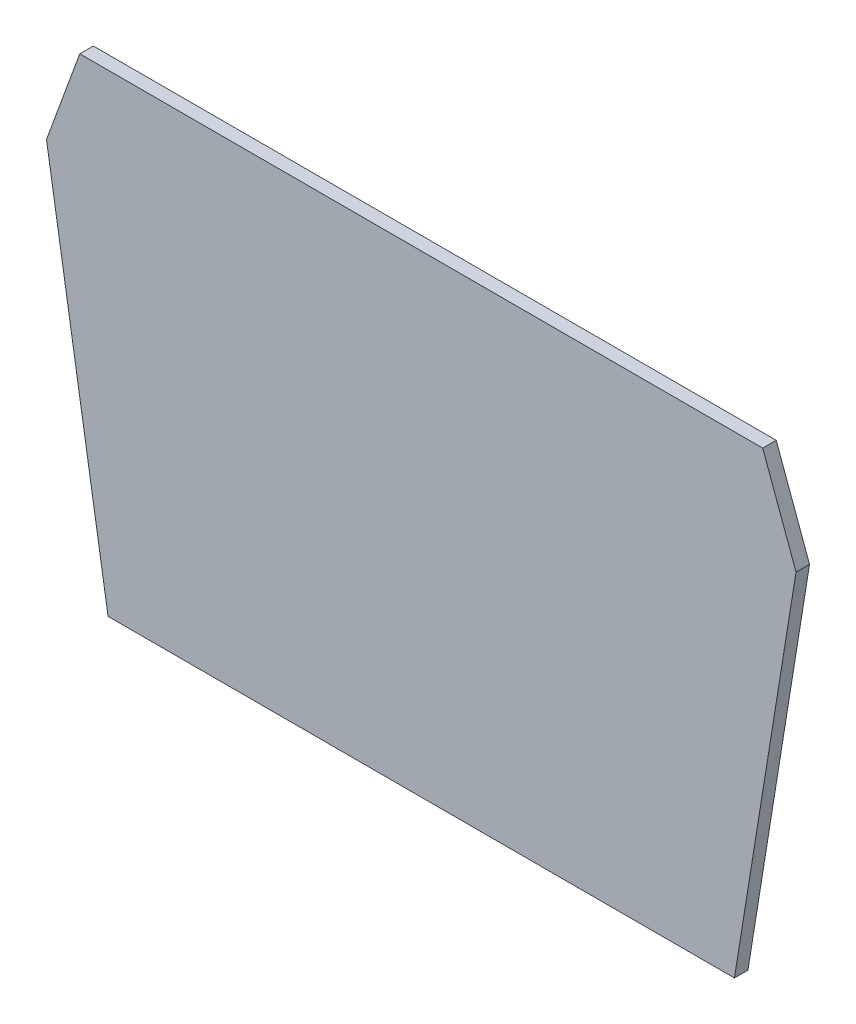
SolidWorks part; units mm, degrees
ref_plane "Front Plane" through (0, 0, 0) normal (0, 0, 1) x (1, 0, 0)
ref_plane "Top Plane" through (0, 0, 0) normal (0, 1, 0) x (1, 0, 0)
ref_plane "Right Plane" through (0, 0, 0) normal (1, 0, 0) x (0, 0, -1)
sketch "Sketch1" plane through (0, 0, 0) normal (0, 0, 1) x (1, 0, 0)
  line L0 (0, 413.7026) -> (0, -30.7974) construction
  line L1 (-320.8365, 413.7026) -> (320.8365, 413.7026)
  line L3 (-294.2767, -30.7974) -> (294.2767, -30.7974)
  line L11 (-294.2767, -30.7974) -> (-352.1464, 328.3868)
  line L13 (-352.1464, 328.3868) -> (-320.8365, 413.7026)
  line L14 (352.1464, 328.3868) -> (320.8365, 413.7026)
  line L15 (294.2767, -30.7974) -> (352.1464, 328.3868)
  dimension "D1" = 294.2767
  dimension "D2" = 359.1842
  dimension "D3" = 57.8697
  dimension "D4" = 90.8796
extrude "Boss-Extrude1" add sketch "Sketch1" along normal blind 12.7
